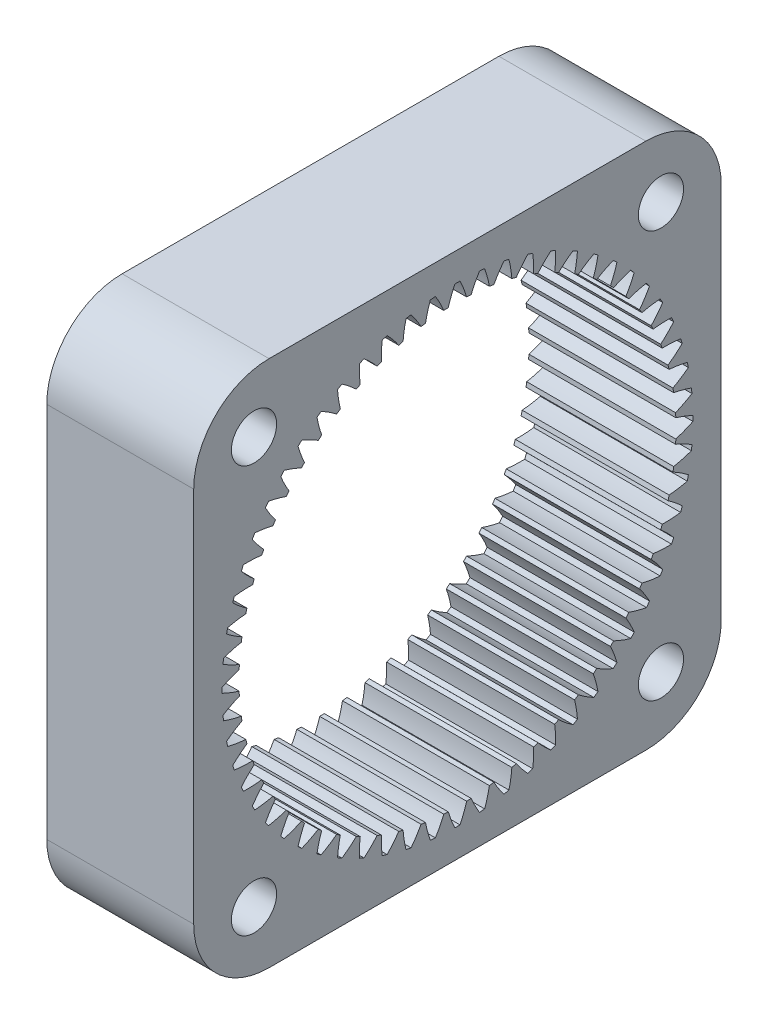
SolidWorks part; units mm, degrees
ref_plane "Plane1" through (0, 0, 0) normal (0, 0, 1) x (1, 0, 0)
ref_plane "Plane2" through (0, 0, 0) normal (0, 1, 0) x (1, 0, 0)
ref_plane "Plane3" through (0, 0, 0) normal (1, 0, 0) x (0, 0, -1)
sketch "HoldingSke" plane through (0, 0, 0) normal (0, 1, 0) x (1, 0, 0)
  line L0 (0, 0) -> (0.5, -0.866)
  line L1 (-15, 0) -> (100, 0) construction
  line L2 (0, 0) -> (-2.1039, 2.3779)
  line L3 (0, 0) -> (-11.863, 4.5341)
  line L4 (0, 0) -> (4.318, 7.479)
  line L5 (0, 0) -> (-23.7986, -8.8762)
  line L6 (0, 0) -> (-10.5278, -7.1032)
  line L7 (-2.1039, 2.3779) -> (3.3635, 27.1825)
  line L8 (-76.2, 3.3779) -> (-54.61, 3.3779)
  line L9 (-71.009, 38.7566) -> (-53.1078, 45.2721)
  line L10 (-76.2, 71.12) -> (104.1128, 71.12)
  line L11 (0, 0) -> (-19.5, 0)
  line L12 (-76.2, 101.6) -> (-76.162, 101.6)
  line L13 (24.9733, 27.94) -> (52.9518, 28.4284)
  line L14 (24.9733, 27.94) -> (24.9743, 27.94)
  line L15 (24.9733, 27.94) -> (100.4006, 29.5858)
  circle A0 centre (0, 0) radius 35
  circle A1 centre (0, 0) radius 12.7
  circle A2 centre (0, 0) radius 12.7
  dimension "MHD" = 25.4
  dimension "Hub_dia" = 25.4
  dimension "Diameter" = 70
  dimension "Num_teeth" = 60
  dimension "Pitch" = 1
  dimension "Overall_len" = 25.4
  dimension "Show_teeth" = 60
  dimension "Thickness" = 12.7
  dimension "OAL" = 25.4001
  dimension "T_dim" = 21.59
  dimension "Ap" = 20
  dimension "H" = 19.05
  dimension "Pitch_radius" = 180.3128
  dimension "Width" = 19.5
  dimension "Backlash" = 0.038
  dimension "Addendum_fac" = 1
  dimension "Dedendum_fac" = 1.25
  dimension "Clearance_fac" = 0.25
  dimension "Dedendum_add" = 0.001
  dimension "Module" = 1
sketch "BasProSke" plane through (0, 0, 0) normal (0, 1, 0) x (1, 0, 0)
  line L0 (-10, 0) -> (60, 0) construction
  line L1 (0, 29) -> (0, 35)
  line L2 (0, 29) -> (19.5, 29)
  line L3 (19.5, 29) -> (19.5, 35)
  line L4 (19.5, 35) -> (0, 35)
  dimension "Diameter" = 70
  dimension "Thickness" = 19.5
  dimension "Inside_diameter" = 58
revolve "Base-Revolve" add sketch "BasProSke" angle 360 about L0
sketch "TooCutSke" plane through (0, 0, 0) normal (1, 0, 0) x (0, 0, -1)
  line L3 (0.8803, 29.9871) -> (0.8803, 53.6633) construction
  line L4 (0, 0) -> (0, 59.563) construction
  line L5 (0, 0) -> (-3.576, 68.2339) construction
  line L6 (-13.1633, 24.7167) -> (36.4631, 27.3175) construction
  circle A0 centre (0, 0) radius 30 construction
  circle A1 centre (0, 0) radius 31.251 construction
  circle A2 centre (0, 0) radius 25.3717 construction
  circle A3 centre (0, 0) radius 28.9746 construction
  arc A4 (1.2274, 28.9486) -> (0.3395, 31.2492) centre (-13.1633, 24.7167) ccw
  arc A5 (1.2274, 28.9486) -> (-1.2274, 28.9486) centre (0, 0) ccw
  arc A6 (0.3395, 31.2492) -> (-0.3395, 31.2492) centre (0, 0) ccw
  arc A7 (-0.3395, 31.2492) -> (-1.2274, 28.9486) centre (13.1633, 24.7167) ccw
  dimension "Pitch_dia" = 60
  dimension "Base_dia" = 50.7434
  dimension "Root_dia" = 62.502
  dimension "Overcut_dia" = 57.9492
  dimension "Flank_rad" = 15
  dimension "Half_ang" = 3
  dimension "Half_CT" = 0.8803
extrude "ToothCut" cut sketch "TooCutSke" along normal through all
fillet "Breaks" [suppressed] radius 0.1
fillet "RootFillets" [suppressed] radius 0.251
pattern_circular "TeethCuts" count 60 every 6 about axis through (-10, 0, 0) along (1, 0, 0) of "RootFillets", "Breaks", "ToothCut"
sketch "Croquis1" plane through (19.5, 0, 0) normal (1, 0, 0) x (0, 0, -1)
  line L1 (-35, 35) -> (35, 35)
  line L2 (-35, 35) -> (-35, -35)
  line L3 (-35, -35) -> (35, -35)
  line L4 (35, 35) -> (35, -35)
  line L5 (-35, 35) -> (35, -35) construction
  line L6 (-35, -35) -> (35, 35) construction
  circle A0 centre (0, 0) radius 35
  dimension "D2" = 70
  dimension "D1" = 70
  dimension "D3" = 70
extrude "Saliente-Extruir1" add sketch "Croquis1" against normal through all contours A0 L1 L2 | A0 L4 L1 | A0 L3 L4 | A0 L2 L3
fillet "Redondeo1" radius 10 4 edges at (9.75, -35, -35) (9.75, 35, 35) (9.75, 35, -35) (9.75, -35, 35)
sketch "Croquis2" plane through (19.5, 0, 0) normal (1, 0, 0) x (0, 0, -1)
  line L0 (-25, -35) -> (25, -35) construction
  line L1 (-35, 25) -> (-35, -25) construction
  line L2 (35, 25) -> (35, -25) construction
  line L3 (-25, 35) -> (25, 35) construction
  circle A0 centre (-27, 27) radius 3
  circle A1 centre (27, 27) radius 3
  circle A2 centre (27, -27) radius 3
  circle A3 centre (-27, -27) radius 3
  dimension "D1" = 6
  dimension "D2" = 6
  dimension "D3" = 6
  dimension "D4" = 6
  dimension "D5" = 8
  dimension "D6" = 8
  dimension "D7" = 8
  dimension "D8" = 8
  dimension "D9" = 8
  dimension "D10" = 8
  dimension "D11" = 8
  dimension "D12" = 8
extrude "Cortar-Extruir1" cut sketch "Croquis2" against normal through all contours A0 | A1 | A2 | A3
equation "' \"Module@HoldingSke\" = 6.35"
equation "' \"Num_teeth@HoldingSke\" = 24"
equation "' \"Ap@HoldingSke\" =  14.5"
equation "' \"Ap@HoldingSke\" = 14.5"
equation "' \"Width@HoldingSke\" = 12"
equation "' \"Diameter@HoldingSke\" = 8 * 25.4"
equation "' \"Show_teeth@HoldingSke\" = 100"
equation "' \"Backlash@HoldingSke\" = 0.009 * 25.4"
equation "' \"Addendum_fac@HoldingSke\" = 1.0"
equation "' \"Dedendum_fac@HoldingSke\" = 1.25"
equation "' \"Dedendum_add@HoldingSke\" = 0.00005 * 25.4"
equation "' \"Clearance_fac@HoldingSke\" = 0.25"
equation "\"Pitch@HoldingSke\" = 1 / \"Module@HoldingSke\" "
equation "\"Overcut_dia@TooCutSke\" = (\"Num_teeth@HoldingSke\" - 2 * \"Addendum_fac@HoldingSke\") / \"Pitch@HoldingSke\" - 0.002 * 25.4"
equation "\"Pitch_dia@TooCutSke\" = \"Num_teeth@HoldingSke\" / \"Pitch@HoldingSke\""
equation "\"Base_dia@TooCutSke\" = \"Num_teeth@HoldingSke\" / \"Pitch@HoldingSke\" * cos((\"Ap@HoldingSke\"  * 3.14159265 / 180)) * 0.90"
equation "\"Root_dia@TooCutSke\" = \"Num_teeth@HoldingSke\"  / \"Pitch@HoldingSke\" + 2 *  \"Dedendum_fac@HoldingSke\"/ \"Pitch@HoldingSke\" + \"Dedendum_add@HoldingSke\" * 2"
equation "\"Half_ang@TooCutSke\" = 180 / \"Num_teeth@HoldingSke\""
equation "\"Half_CT@TooCutSke\" = \"Num_teeth@HoldingSke\" / \"Pitch@HoldingSke\" * sin((3.14159265 / 2 / \"Num_teeth@HoldingSke\")) / 2 + 10 * \"Backlash@HoldingSke\" / 4"
equation "\"Flank_rad@TooCutSke\" = \"Num_teeth@HoldingSke\" / \"Pitch@HoldingSke\" / 4"
equation "\"Radius@RootFillets\"= \"Clearance_fac@HoldingSke\" / \"Pitch@HoldingSke\" + \"Dedendum_add@HoldingSke\""
equation "\"Break_rad@Breaks\" = 0.02 / \"Pitch@HoldingSke\" * 5"
equation "\"Num_teeth@TeethCuts\" = int( \"Show_teeth@HoldingSke\" ) + 1"
equation "\"Num_teeth@TeethCuts\" = ((sgn( \"Num_teeth@TeethCuts\" - \"Num_teeth@HoldingSke\" )-1)*( \"Num_teeth@TeethCuts\" - \"Num_teeth@HoldingSke\" ))/-2+ \"Num_teeth@HoldingSke\""
equation "\"Num_teeth@TeethCuts\" = ((sgn( \"Num_teeth@TeethCuts\" - 2.0)+1)*( \"Num_teeth@TeethCuts\" - 2.0))/2 +2.0"
equation "\"Angle@TeethCuts\" = 360.0 / \"Num_teeth@HoldingSke\""
equation "\"Diameter@BasProSke\" = \"Num_teeth@HoldingSke\"  / \"Pitch@HoldingSke\" + 2 *  \"Dedendum_fac@HoldingSke\"/ \"Pitch@HoldingSke\" + \"Dedendum_add@HoldingSke\" * 2 + 0.002 * 25.4"
equation "\"Diameter@BasProSke\" = ((sgn( \"Diameter@BasProSke\"  - \"Diameter@HoldingSke\" )+1)*( \"Diameter@BasProSke\"  - \"Diameter@HoldingSke\" ))/2 + \"Diameter@HoldingSke\""
equation "\"Inside_diameter@BasProSke\" =  (\"Num_teeth@HoldingSke\" - 2 * \"Addendum_fac@HoldingSke\") / \"Pitch@HoldingSke\" "
equation "\"Thickness@BasProSke\"  = \"Width@HoldingSke\""
